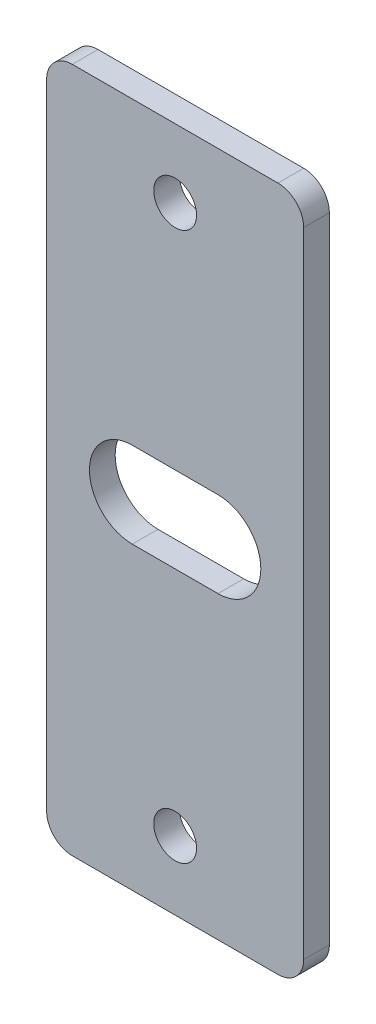
SolidWorks part; units mm, degrees
ref_plane "前视基准面" through (0, 0, 0) normal (0, 0, 1) x (1, 0, 0)
ref_plane "上视基准面" through (0, 0, 0) normal (0, 1, 0) x (1, 0, 0)
ref_plane "右视基准面" through (0, 0, 0) normal (1, 0, 0) x (0, 0, -1)
sketch "草图1" plane through (0, 0, 0) normal (0, 0, 1) x (1, 0, 0)
  line L0 (-12, 0) -> (12, 0)
  line L1 (15, 3) -> (15, 77)
  line L2 (12, 80) -> (-12, 80)
  line L3 (-15, 77) -> (-15, 3)
  arc A0 (-15, 3) -> (-12, 0) centre (-12, 3) ccw
  arc A1 (12, 0) -> (15, 3) centre (12, 3) ccw
  arc A2 (15, 77) -> (12, 80) centre (12, 77) ccw
  arc A3 (-12, 80) -> (-15, 77) centre (-12, 77) ccw
extrude "凸台-拉伸1" add sketch "草图1" along normal blind 3
sketch "草图2" plane through (0, 0, 0) normal (0, 0, 1) x (1, 0, 0)
  line L0 (-5, 35) -> (5, 35)
  line L1 (5, 45) -> (-5, 45)
  circle A0 centre (0, 8) radius 2.5
  circle A1 centre (0, 72) radius 2.5
  arc A2 (5, 35) -> (5, 45) centre (5, 40) ccw
  arc A3 (-5, 45) -> (-5, 35) centre (-5, 40) ccw
extrude "切除-拉伸1" cut sketch "草图2" along normal through all
